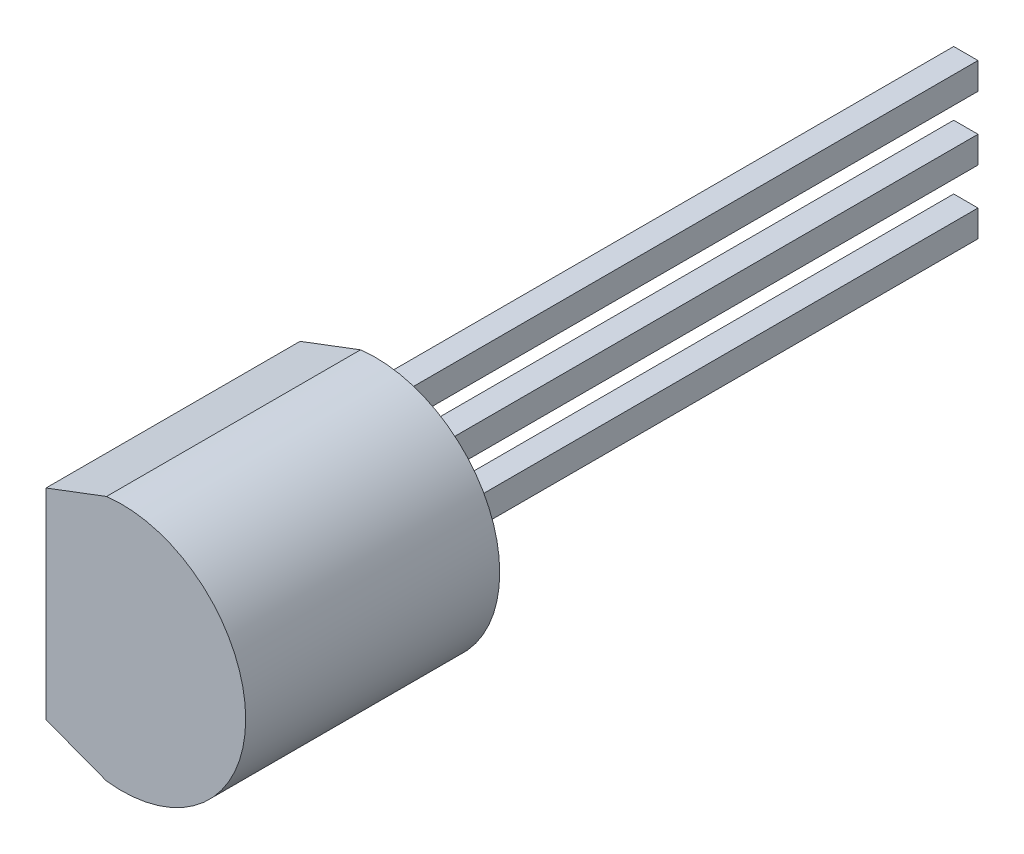
SolidWorks part; units mm, degrees
ref_plane "Plan de face" through (0, 0, 0) normal (0, 0, 1) x (1, 0, 0)
ref_plane "Plan de dessus" through (0, 0, 0) normal (0, 1, 0) x (1, 0, 0)
ref_plane "Plan de droite" through (0, 0, 0) normal (1, 0, 0) x (0, 0, -1)
sketch "Esquisse1" plane through (0, 0, 0) normal (0, 0, 1) x (1, 0, 0)
  line L0 (-1.27, 2.105) -> (-1.27, -2.105)
  line L1 (-1.27, 2.105) -> (0, 2.5859)
  line L2 (0, -2.5859) -> (-1.27, -2.105)
  line L3 (0, 2.5859) -> (0, -2.5859) construction
  line L4 (0, 0) -> (-6.8292, 0) construction
  line L5 (-6.8292, 0) -> (-1.27, 2.105) construction
  line L6 (-1.27, -2.105) -> (-6.8292, 0) construction
  line L7 (0, 0) -> (2.92, 0) construction
  line L8 (0.315, 2.605) -> (0.315, -2.605) construction
  arc A0 (0, 2.5859) -> (0, -2.5859) centre (0.315, 0) cw
  dimension "D1" = 2.92
  dimension "D2" = 4.19
  dimension "D3" = 5.21
  dimension "D4" = 4.21
extrude "Boss.-Extru.1" add sketch "Esquisse1" along normal blind 5.33
sketch "Esquisse2" plane through (0, 0, 0) normal (0, 0, -1) x (-1, 0, 0)
  line L0 (0, 1.34) -> (0, 0) construction
  line L1 (0.255, 1.62) -> (-0.255, 1.62)
  line L2 (0.255, 1.62) -> (0.255, 1.06)
  line L3 (0.255, 1.06) -> (-0.255, 1.06)
  line L4 (-0.255, 1.62) -> (-0.255, 1.06)
  line L5 (0.255, 1.62) -> (-0.255, 1.06) construction
  line L6 (0.255, 1.06) -> (-0.255, 1.62) construction
  line L7 (0.255, 0.28) -> (-0.255, 0.28)
  line L8 (0.255, 0.28) -> (0.255, -0.28)
  line L9 (0.255, -0.28) -> (-0.255, -0.28)
  line L10 (-0.255, 0.28) -> (-0.255, -0.28)
  line L11 (0.255, 0.28) -> (-0.255, -0.28) construction
  line L12 (0.255, -0.28) -> (-0.255, 0.28) construction
  line L13 (0.255, -1.06) -> (-0.255, -1.06)
  line L14 (0.255, -1.06) -> (0.255, -1.62)
  line L15 (0.255, -1.62) -> (-0.255, -1.62)
  line L16 (-0.255, -1.06) -> (-0.255, -1.62)
  line L17 (0.255, -1.06) -> (-0.255, -1.62) construction
  line L18 (0.255, -1.62) -> (-0.255, -1.06) construction
  line L19 (0, 0) -> (0, -1.34) construction
  point P0 (0, 1.34)
  point P5 (0, 0)
  point P11 (0, -1.34)
  dimension "D1" = 0.51
  dimension "D2" = 0.56
  dimension "D3" = 2.68
extrude "Boss.-Extru.2" add sketch "Esquisse2" along normal blind 12.7
